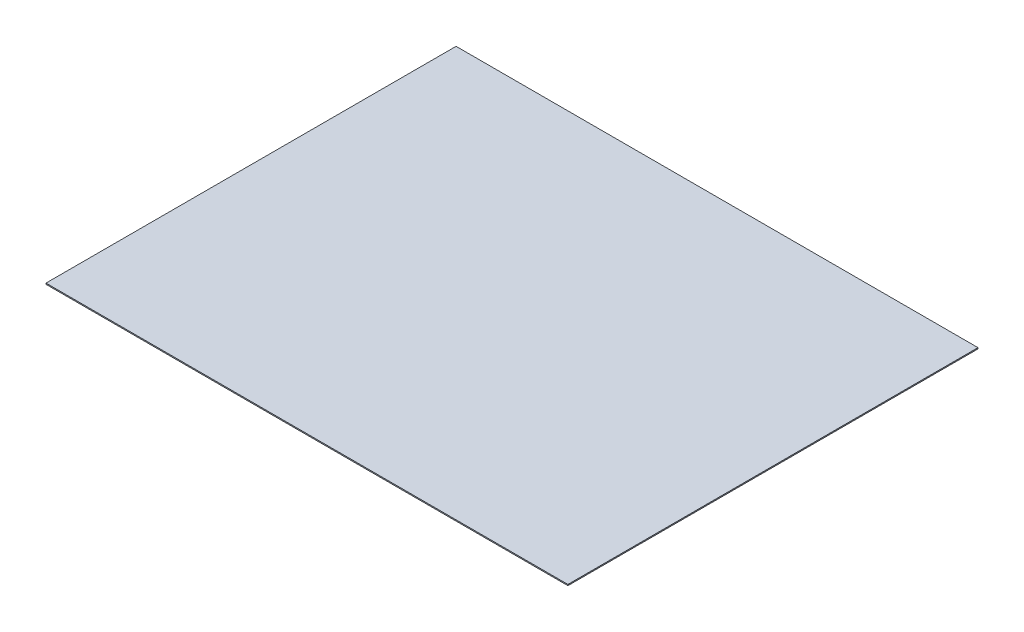
SolidWorks part; units mm, degrees
material "Thornel Mat VMA"
ref_plane "Front Plane" through (0, 0, 0) normal (0, 0, 1) x (1, 0, 0)
ref_plane "Top Plane" through (0, 0, 0) normal (0, 1, 0) x (1, 0, 0)
ref_plane "Right Plane" through (0, 0, 0) normal (1, 0, 0) x (0, 0, -1)
sketch "Sketch1" plane through (0, 0, 0) normal (0, 1, 0) x (1, 0, 0)
  line L1 (350, -275) -> (-350, -275)
  line L2 (350, -275) -> (350, 275)
  line L3 (350, 275) -> (-350, 275)
  line L4 (-350, -275) -> (-350, 275)
  line L5 (350, -275) -> (-350, 275) construction
  line L6 (350, 275) -> (-350, -275) construction
  point P0 (0, 0)
  dimension "D1" = 700
  dimension "D2" = 550
extrude "Boss-Extrude1" add sketch "Sketch1" along normal blind 1.5
